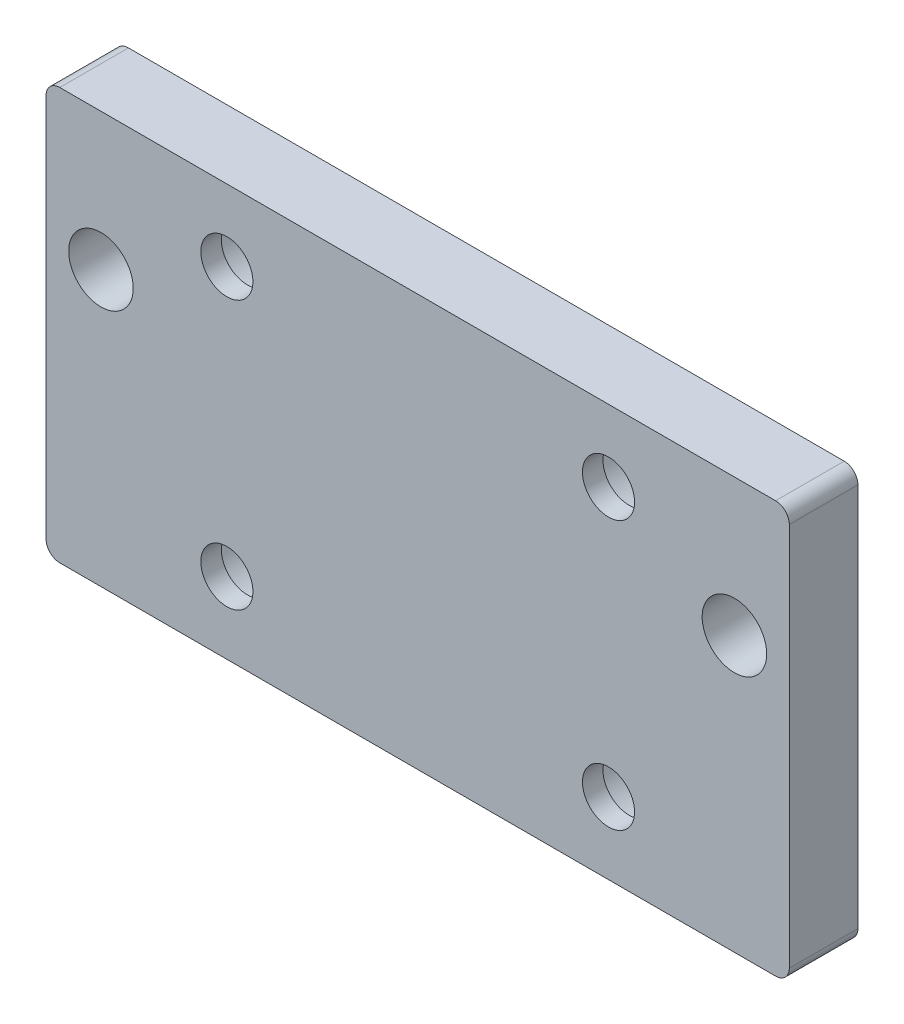
SolidWorks part; units mm, degrees
material "ABS"
ref_plane "Front Plane" through (0, 0, 0) normal (0, 0, 1) x (1, 0, 0)
ref_plane "Top Plane" through (0, 0, 0) normal (0, 1, 0) x (1, 0, 0)
ref_plane "Right Plane" through (0, 0, 0) normal (1, 0, 0) x (0, 0, -1)
sketch "Sketch1" plane through (0, 0, 0) normal (0, 0, 1) x (1, 0, 0)
  line L1 (0, 0) -> (54.161, 0)
  line L2 (0, 0) -> (0, 30)
  line L3 (0, 30) -> (54.161, 30)
  line L4 (54.161, 0) -> (54.161, 30)
  dimension "D1" = 30
  dimension "D2" = 54.161
extrude "Boss-Extrude1" add sketch "Sketch1" along normal blind 5
hole_wizard "M4 Clearance Hole1" positions "Sketch2" profile "Sketch4" hole size "M4" standard "ANSI Metric" end condition up to next
sketch "Sketch2" plane through (0, 0, 5) normal (0, 0, 1) x (1, 0, 0)
  line L0 (0, 30) -> (0, 0) construction
  line L1 (54.161, 0) -> (54.161, 30) construction
  line L2 (54.161, 30) -> (0, 30) construction
  point P0 (4, 20)
  point P2 (50.161, 20)
  dimension "D1" = 4
  dimension "D2" = 4
  dimension "D3" = 10
sketch "Sketch4" plane through (4, 20, 5) normal (1, 0, 0) x (0, -1, 0)
  line L0 (0, 0) -> (0, 5)
  line L1 (0, 5) -> (2.35, 5)
  line L2 (2.35, 5) -> (2.35, 0)
  line L5 (2.35, 0) -> (0, 0)
  line L11 (0, -6.35) -> (0, 107.95) construction
  dimension "Thru Hole Dia." = 4.7
  dimension "Thru Hole Depth" = 5
fillet "Fillet1" radius 1 4 edges at (54.161, 30, 2.5) (54.161, 0, 2.5) (0, 0, 2.5) (0, 30, 2.5)
hole_wizard "CBORE for #6 Socket Head Cap Screw1" positions "Sketch7" profile "Sketch8" counterbore size "#6" standard "ANSI Inch" end condition up to next
sketch "Sketch7" plane through (0, 0, 0) normal (0, 0, -1) x (-1, 0, 0)
  point P0 (-40.986, 24.779)
  point P3 (-13.175, 24.779)
  point P6 (-40.986, 5.221)
  point P9 (-13.175, 5.221)
sketch "Sketch8" plane through (40.986, 24.779, 0) normal (1, 0, 0) x (0, 1, 0)
  line L0 (0, 0) -> (0, 5)
  line L1 (0, 5) -> (1.8986, 5)
  line L3 (1.8986, 5) -> (1.8986, 3.5052)
  line L4 (1.8986, 3.5052) -> (3.5725, 3.5052)
  line L5 (3.5725, 3.5052) -> (3.5725, 0)
  line L7 (3.5725, 0) -> (0, 0)
  line L11 (0, -6.35) -> (0, 107.95) construction
  dimension "Thru Hole Dia." = 3.7973
  dimension "Thru Hole Depth" = 5
  dimension "C'Bore Dia." = 7.145
  dimension "C'Bore Depth" = 3.5052
